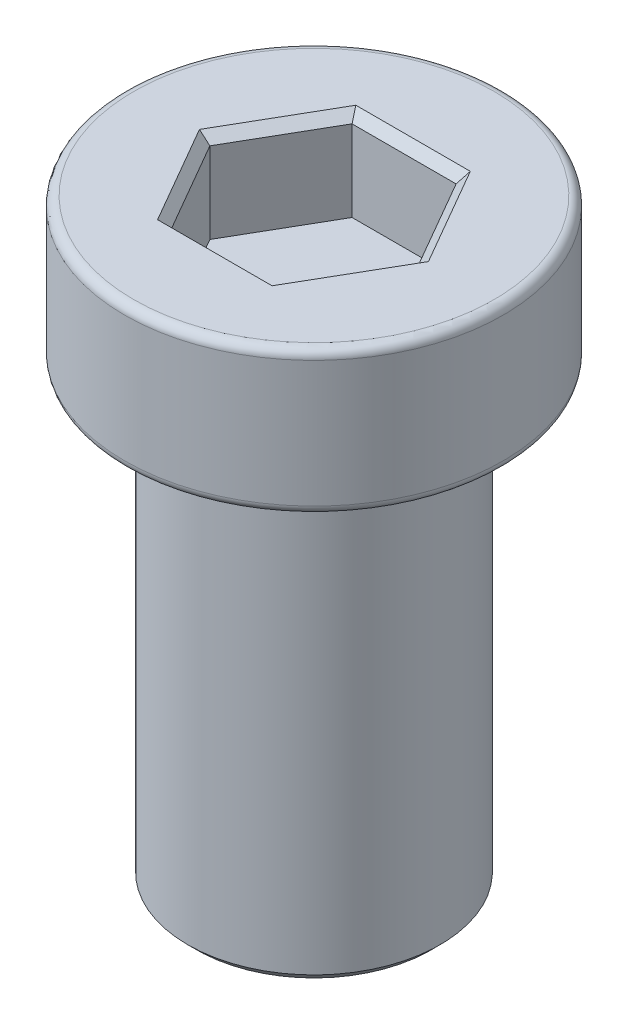
SolidWorks part; units mm, degrees
material "AISI 304"
ref_plane "前视基准面" through (0, 0, 0) normal (0, 0, 1) x (1, 0, 0)
ref_plane "上视基准面" through (0, 0, 0) normal (0, 1, 0) x (1, 0, 0)
ref_plane "右视基准面" through (0, 0, 0) normal (1, 0, 0) x (0, 0, -1)
sketch "草图1" plane through (0, 0, 0) normal (0, 1, 0) x (1, 0, 0)
  circle A0 centre (0, 0) radius 10.5
  dimension "D1" = 21
extrude "凸台-拉伸1" add sketch "草图1" along normal blind 8
sketch "草图2" plane through (0, 0, 0) normal (0, -1, 0) x (1, 0, 0)
  circle A0 centre (0, 0) radius 7
  dimension "D1" = 14
extrude "凸台-拉伸2" add sketch "草图2" along normal blind 25
cosmetic thread "装饰螺纹线1" parameters "D2"=11.835
sketch "草图3" plane through (0, 8, 0) normal (0, 1, 0) x (1, 0, 0)
  line L1 (5.7735, 0) -> (2.8868, 5)
  line L2 (2.8868, 5) -> (-2.8868, 5)
  line L3 (-2.8868, 5) -> (-5.7735, 0)
  line L4 (-5.7735, 0) -> (-2.8868, -5)
  line L5 (-2.8868, -5) -> (2.8868, -5)
  line L6 (2.8868, -5) -> (5.7735, 0)
  circle A0 centre (0, 0) radius 5 construction
  dimension "D1" = 10
extrude "切除-拉伸1" cut sketch "草图3" against normal blind 5
chamfer "倒角1" distance 0.5 angle 45 1 edges at (0, -25, -7)
fillet "圆角1" radius 0.5 2 edges at (0, 8, 10.5) (0, 0, 10.5)
chamfer "倒角2" distance 0.5 angle 45 6 edges at (4.3301, 8, 2.5) (0, 8, 5) (-4.3301, 8, 2.5) (4.3301, 8, -2.5) (0, 8, -5) (-4.3301, 8, -2.5)
